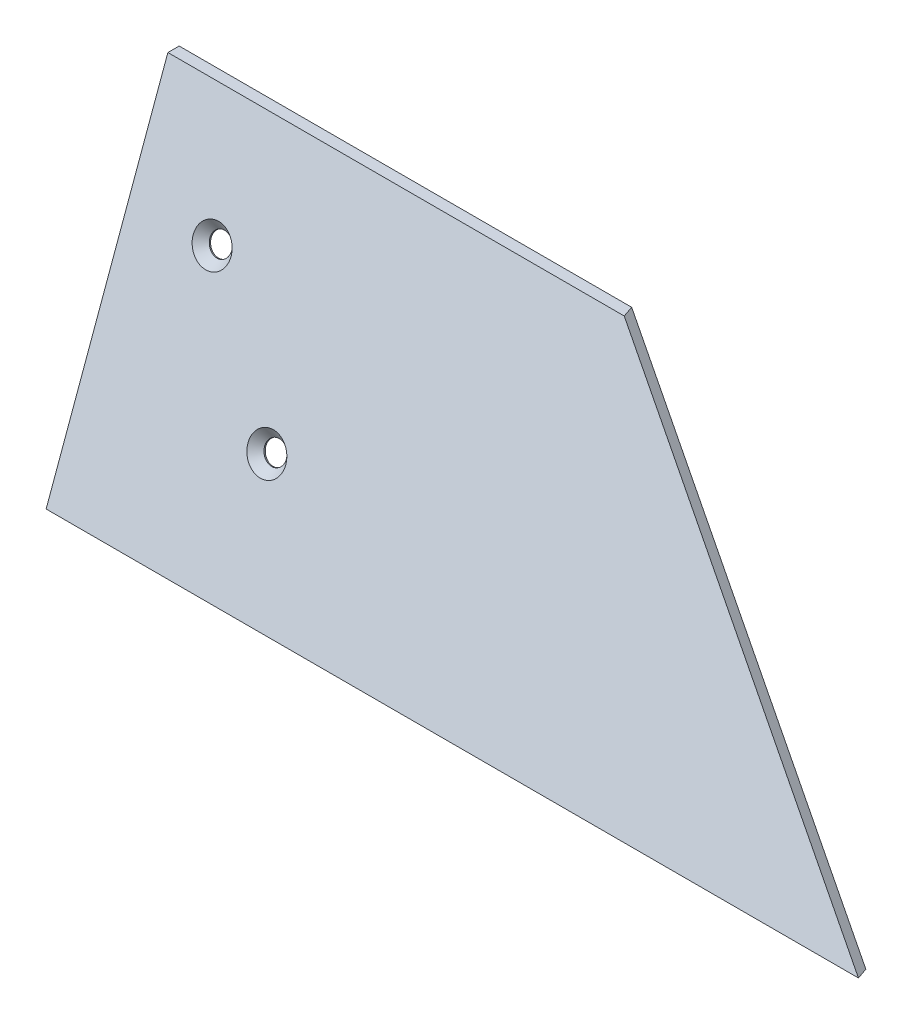
SolidWorks part; units mm, degrees
ref_plane "Front Plane" through (0, 0, 0) normal (0, 0, 1) x (1, 0, 0)
ref_plane "Top Plane" through (0, 0, 0) normal (0, 1, 0) x (1, 0, 0)
ref_plane "Right Plane" through (0, 0, 0) normal (1, 0, 0) x (0, 0, -1)
sketch "Sketch1" plane through (0, 0, 0) normal (1, 0, 0) x (0, 0, -1)
  line L0 (0, 0) -> (-2.3622, 0)
  line L1 (-2.3622, 0) -> (23.1157, 70)
  line L2 (23.1157, 70) -> (25.4779, 70)
  line L3 (25.4779, 70) -> (0, 0)
  dimension "D1" = 2.3622
  dimension "D2" = 2.3622
  dimension "D3" = 70
  dimension "D4" = 70
extrude "Main" add sketch "Sketch1" along normal mid plane 170
hole_wizard "BackBracketHoles" positions "Sketch2" profile "Sketch3" countersink size "#8" standard "ANSI Inch"
sketch "Sketch2" plane through (0, 0.7592, 2.0859) normal (0, 0.342, 0.9397) x (1, 0, 0)
  line L0 (-85, 73.6845) -> (-85, -0.8079) construction
  line L1 (85, -0.8079) -> (-85, -0.8079) construction
  point P0 (-67.6378, 50.0021)
  point P2 (-47.6378, 25.0021)
  point P13 (0, 0)
  dimension "D1" = 17.3622
  dimension "D2" = 50.81
  dimension "D3" = 25.81
  dimension "D4" = 37.3622
sketch "Sketch3" plane through (-67.6378, 47.7458, -15.0158) normal (1, 0, 0) x (0, -0.9397, 0.342)
  line L0 (0, 0) -> (0, 5)
  line L1 (0, 5) -> (2.286, 5)
  line L2 (2.286, 5) -> (2.286, 1.9285)
  line L3 (2.286, 1.9285) -> (3.9624, 0)
  line L5 (3.9624, 0) -> (0, 0)
  line L6 (-2.286, 1.9285) -> (-3.9624, 0) construction
  line L10 (0, 5) -> (-2.286, 5) construction
  line L11 (0, -6.35) -> (0, 107.95) construction
  dimension "Hole Dia." = 4.572
  dimension "Hole Depth" = 5
  dimension "Near C'Sink Dia." = 7.9248
  dimension "Near C'Sink Angle" = 82
  dimension "Drill Angle" = 180
sketch "Sketch4" plane through (0, 0.7592, 2.0859) normal (0, 0.342, 0.9397) x (1, 0, 0)
  line L0 (85, -0.8079) -> (9.6996, 74.4924)
  line L1 (85, 74.4924) -> (-85, 74.4924) construction
  line L2 (9.6996, 74.4924) -> (85, 74.4924)
  line L3 (85, 74.4924) -> (85, -0.8079)
  dimension "D1" = 45
extrude "Front Cut" cut sketch "Sketch4" against normal up to next
